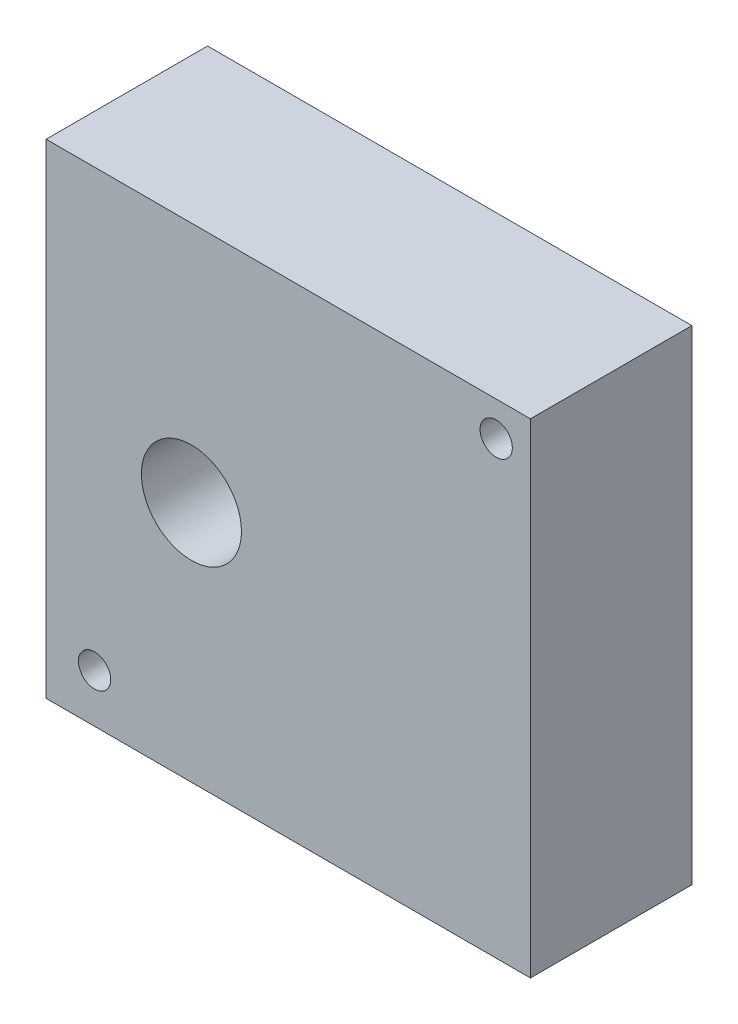
SolidWorks part; units mm, degrees
ref_plane "Front Plane" through (0, 0, 0) normal (0, 0, 1) x (1, 0, 0)
ref_plane "Top Plane" through (0, 0, 0) normal (0, 1, 0) x (1, 0, 0)
ref_plane "Right Plane" through (0, 0, 0) normal (1, 0, 0) x (0, 0, -1)
sketch "Sketch1" plane through (0, 0, 0) normal (0, 0, 1) x (1, 0, 0)
  line L1 (-15, 15) -> (15, 15)
  line L2 (-15, 15) -> (-15, -15)
  line L3 (-15, -15) -> (15, -15)
  line L4 (15, 15) -> (15, -15)
  line L5 (-15, 15) -> (15, -15) construction
  line L6 (-15, -15) -> (15, 15) construction
  point P0 (0, 0)
  dimension "D1" = 30
  dimension "D2" = 30
extrude "Boss-Extrude1" add sketch "Sketch1" along normal blind 10
sketch "Sketch2" plane through (0, 0, 10) normal (0, 0, 1) x (1, 0, 0)
  line L1 (-15, 15) -> (15, 15)
  line L2 (-15, 15) -> (-15, -15)
  line L3 (-15, -15) -> (15, -15)
  line L4 (15, 15) -> (15, -15)
  line L5 (-15, 15) -> (15, -15) construction
  line L6 (-15, -15) -> (15, 15) construction
  line L7 (10, 10) -> (-10, 10)
  line L8 (10, 10) -> (10, -10)
  line L9 (10, -10) -> (-10, -10)
  line L10 (-10, 10) -> (-10, -10)
  line L11 (10, 10) -> (-10, -10) construction
  line L12 (10, -10) -> (-10, 10) construction
  line L13 (0, 0) -> (0, -3.5) construction
  line L14 (0, 0) -> (0, 3.5) construction
  line L15 (-2.5, 7.2488) -> (2.5, 7.2488)
  line L16 (-2.5, 7.2488) -> (-2.5, -7.2488)
  line L17 (-2.5, -7.2488) -> (2.5, -7.2488)
  line L18 (2.5, 7.2488) -> (2.5, -7.2488)
  line L19 (-2.5, 7.2488) -> (2.5, -7.2488) construction
  line L20 (-2.5, -7.2488) -> (2.5, 7.2488) construction
  line L21 (-2.5, 3.5) -> (2.5, 3.5)
  line L22 (-2.5, 3.5) -> (-2.5, -3.5)
  line L23 (-2.5, -3.5) -> (2.5, -3.5)
  line L24 (2.5, 3.5) -> (2.5, -3.5)
  line L25 (-2.5, 3.5) -> (2.5, -3.5) construction
  line L26 (-2.5, -3.5) -> (2.5, 3.5) construction
  point P0 (0, 0)
  point P7 (0, 0)
  line M18 (15, -15) -> (15, 15)
  line M19 (15, 15) -> (-15, 15)
  line M20 (-15, 15) -> (-15, -15)
  line M21 (-15, -15) -> (15, -15)
  dimension "D1" = 20
  dimension "D2" = 20
  dimension "D3" = 3.5
  dimension "D4" = 3.5
  dimension "D5" = 7
  dimension "D6" = 5
  dimension "D7" = 5
extrude "Boss-Extrude2" add sketch "Sketch2" along normal blind 10 separate body contours L10 L7 L8 L9 M21 M18 M19 M20 | L16 L21 L18 L15 | L23 L16 L17 L18
sketch "Sketch3" plane through (0, 0, 20) normal (0, 0, 1) x (1, 0, 0)
  line L1 (-15, 15) -> (15, 15)
  line L2 (-15, 15) -> (-15, -15)
  line L3 (-15, -15) -> (15, -15)
  line L4 (15, 15) -> (15, -15)
extrude "Boss-Extrude3" add sketch "Sketch3" along normal blind 10 separate body
sketch "Sketch4" plane through (0, 0, 30) normal (0, 0, 1) x (1, 0, 0)
  line L1 (-15, 15) -> (-15, -15) construction
  line L3 (-15, 0) -> (-6, 0) construction
  circle A0 centre (-6, 0) radius 3.1
  dimension "D1" = 9
sketch "Sketch5" plane through (0, 0, 0) normal (0, 0, -1) x (-1, 0, 0)
  line L0 (-15, -0.3729) -> (-6, -0.3729) construction
  line L1 (-15, -15) -> (-15, 15) construction
  circle A0 centre (-6, -0.3729) radius 3.1
  dimension "D1" = 9
extrude "Cut-Extrude1" cut sketch "Sketch4" against normal blind 10
extrude "Cut-Extrude2" cut sketch "Sketch5" against normal blind 10 contours A0
sketch "Sketch8" plane through (0, 0, 30) normal (0, 0, 1) x (1, 0, 0)
  line L0 (-15, -15) -> (-12, -12) construction
  line L1 (-15, -15) -> (15, -15) construction
  line L2 (15, 15) -> (12.8787, 12.8787) construction
  line L3 (15, 15) -> (-15, 15) construction
  circle A0 centre (-12, -12) radius 1
  circle A1 centre (12.8787, 12.8787) radius 1
  dimension "D1" = 3
  dimension "D2" = 45
  dimension "D3" = 3
  dimension "D4" = 45
extrude "Cut-Extrude3" cut sketch "Sketch8" against normal up to surface (30 mm away)
delete or keep bodies "Body-Delete/Keep 1" type delete bodies bodies 112 110
delete or keep bodies "Body-Delete/Keep 2" type delete bodies bodies 103 104
